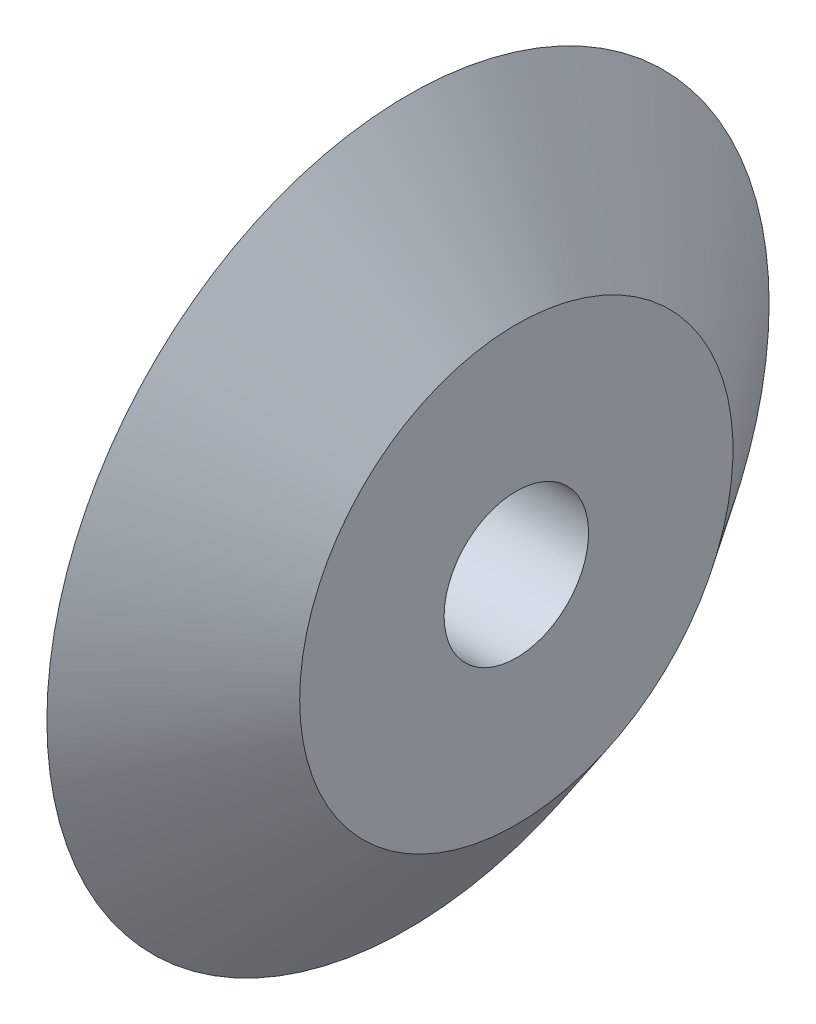
SolidWorks part; units mm, degrees
ref_plane "Front Plane" through (0, 0, 0) normal (0, 0, 1) x (1, 0, 0)
ref_plane "Top Plane" through (0, 0, 0) normal (0, 1, 0) x (1, 0, 0)
ref_plane "Right Plane" through (0, 0, 0) normal (1, 0, 0) x (0, 0, -1)
sketch "Sketch2" plane through (0, 0, 0) normal (0, 0, 1) x (1, 0, 0)
  line L0 (0, 10) -> (0, 50)
  line L1 (0, 50) -> (15, 30)
  line L2 (15, 30) -> (15, 10)
  line L3 (15, 10) -> (0, 10)
  line L4 (0, 0) -> (15, 0) construction
  dimension "D1" = 10
  dimension "D2" = 30
  dimension "D3" = 50
  dimension "D4" = 15
revolve "Revolve1" add sketch "Sketch2" angle 360 about L4
